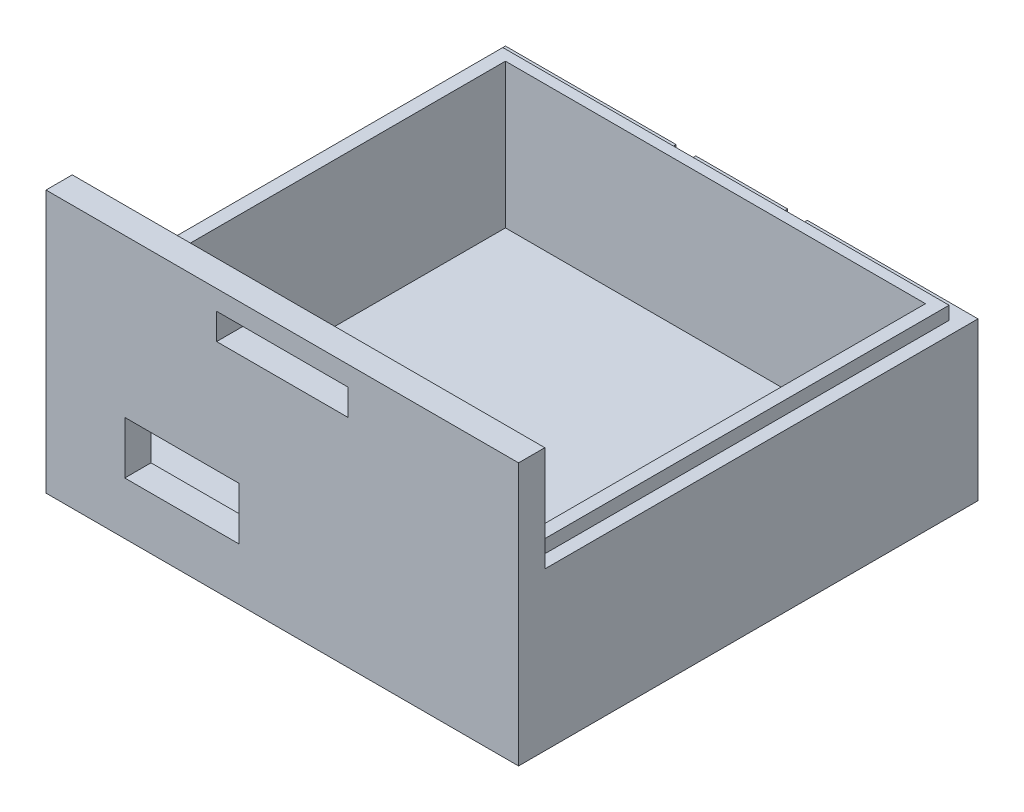
SolidWorks part; units mm, degrees
ref_plane "Alzado" through (0, 0, 0) normal (0, 0, 1) x (1, 0, 0)
ref_plane "Planta" through (0, 0, 0) normal (0, 1, 0) x (1, 0, 0)
ref_plane "Vista lateral" through (0, 0, 0) normal (1, 0, 0) x (0, 0, -1)
sketch "Croquis1" plane through (0, 0, 0) normal (0, 1, 0) x (1, 0, 0)
  line L1 (-18, -17.5) -> (18, -17.5)
  line L2 (-18, -17.5) -> (-18, 17.5)
  line L3 (-18, 17.5) -> (18, 17.5)
  line L4 (18, -17.5) -> (18, 17.5)
  line L5 (-18, -17.5) -> (18, 17.5) construction
  line L6 (-18, 17.5) -> (18, -17.5) construction
  point P0 (0, 0)
  dimension "D1" = 36
  dimension "D2" = 35
extrude "Saliente-Extruir1" add sketch "Croquis1" along normal blind 20
sketch "Croquis2" plane through (0, 20, 0) normal (0, 1, 0) x (1, 0, 0)
  line L1 (-18, -15.5) -> (18, -15.5)
  line L2 (-18, 17.5) -> (-18, -17.5) construction
  line L3 (18, -17.5) -> (18, 17.5) construction
  line L4 (18, -15.5) -> (18, 17.5)
  line L5 (18, 17.5) -> (-18, 17.5)
  line L6 (-18, 17.5) -> (-18, -15.5)
  line L8 (-18, -17.5) -> (18, -17.5) construction
  dimension "D1" = 2
extrude "Cortar-Extruir1" cut sketch "Croquis2" against normal blind 7
sketch "Croquis3" plane through (0, 13, 0) normal (0, 1, 0) x (1, 0, 0)
  line L0 (-16, -15.5) -> (16, -15.5)
  line L1 (-18, -15.5) -> (18, -15.5) construction
  line L2 (-18, -15.5) -> (18, -15.5) construction
  line L3 (16, -15.5) -> (16, 15.5)
  line L4 (16, 15.5) -> (-16, 15.5)
  line L5 (-16, 15.5) -> (-16, -15.5)
  line L6 (-18, 17.5) -> (-18, -15.5) construction
  line L7 (18, 17.5) -> (-18, 17.5) construction
  line L8 (18, -15.5) -> (18, 17.5) construction
  dimension "D1" = 2
  dimension "D2" = 2
  dimension "D3" = 2
extrude "Cortar-Extruir2" cut sketch "Croquis3" against normal blind 11
sketch "Croquis4" plane through (0, 0, 17.5) normal (0, 0, 1) x (1, 0, 0)
  line L1 (-12, 4) -> (-3.3, 4)
  line L2 (-12, 4) -> (-12, 8)
  line L3 (-12, 8) -> (-3.3, 8)
  line L4 (-3.3, 4) -> (-3.3, 8)
  line L5 (-12, 4) -> (-3.3, 8) construction
  line L6 (-12, 8) -> (-3.3, 4) construction
  line L7 (-18, 0) -> (18, 0) construction
  line L8 (-18, 20) -> (-18, 0) construction
  point P0 (-7.65, 6)
  dimension "D1" = 8.7
  dimension "D2" = 6
  dimension "D3" = 8
  dimension "D4" = 4
extrude "Cortar-Extruir3" cut sketch "Croquis4" against normal up to next
sketch "Croquis5" plane through (0, 0, 17.5) normal (0, 0, 1) x (1, 0, 0)
  line L0 (-18, 20) -> (18, 20) construction
  line L1 (-5, 17.5) -> (5, 17.5)
  line L2 (-5, 17.5) -> (-5, 16.5)
  line L3 (-5, 16.5) -> (5, 16.5)
  line L4 (5, 17.5) -> (5, 16.5)
  line L5 (-5, 17.5) -> (5, 16.5) construction
  line L6 (-5, 16.5) -> (5, 17.5) construction
  point P0 (0, 17)
  point P7 (0, 0)
  dimension "D1" = 2.5
  dimension "D2" = 10
  dimension "D3" = 1
extrude "Cortar-Extruir4" cut sketch "Croquis5" against normal up to next
sketch "Croquis6" plane through (0, 0, 17.5) normal (0, 0, 1) x (1, 0, 0)
  line L0 (5, 17.5) -> (-5, 17.5) construction
  line L1 (-5, 18.5) -> (5, 18.5)
  line L2 (-5, 18.5) -> (-5, 17.5)
  line L3 (-5, 17.5) -> (5, 17.5)
  line L4 (5, 18.5) -> (5, 17.5)
  line L5 (-5, 18.5) -> (5, 17.5) construction
  line L6 (-5, 17.5) -> (5, 18.5) construction
  line L7 (-5, 17.5) -> (-5, 16.5) construction
  line L8 (5, 16.5) -> (5, 17.5) construction
  point P0 (0, 18)
  dimension "D1" = 1
extrude "Cortar-Extruir5" cut sketch "Croquis6" against normal blind 1
sketch "Croquis7" plane through (0, 13, 0) normal (0, 1, 0) x (1, 0, 0)
  line L0 (-18, -15.5) -> (-17, -15.5)
  line L1 (-18, -15.5) -> (-16, -15.5) construction
  line L2 (-17, -15.5) -> (-17, 16.3)
  line L3 (-17, 16.3) -> (17, 16.3)
  line L4 (17, 16.3) -> (17, -15.5)
  line L5 (16, -15.5) -> (18, -15.5) construction
  line L6 (17, -15.5) -> (18, -15.5)
  line L7 (18, -15.5) -> (18, 17.5)
  line L8 (18, 17.5) -> (-18, 17.5)
  line L9 (-18, 17.5) -> (-18, -15.5)
  dimension "D1" = 1.2
extrude "Cortar-Extruir6" cut sketch "Croquis7" against normal blind 1
sketch "Croquis8" plane through (0, 0, -17.5) normal (0, 0, -1) x (-1, 0, 0)
  line L0 (-5, 12) -> (-5, 7)
  line L1 (-18, 12) -> (18, 12) construction
  line L2 (-5, 7) -> (5, 7)
  line L3 (5, 7) -> (5, 12)
  line L4 (17, 12) -> (-17, 12) construction
  line L5 (5, 12) -> (3.5, 12)
  line L6 (3.5, 12) -> (3.5, 9)
  line L7 (3.5, 9) -> (-3.5, 9)
  line L8 (-3.5, 9) -> (-3.5, 12)
  line L9 (-3.5, 12) -> (-5, 12)
  point P12 (0, 9)
  point P13 (0, 7)
  dimension "D1" = 10
  dimension "D2" = 7
  dimension "D3" = 2
  dimension "D4" = 5
extrude "Cortar-Extruir7" cut sketch "Croquis8" against normal up to surface (1.2 mm away) up to face at (0, 12.5, -16.3)
